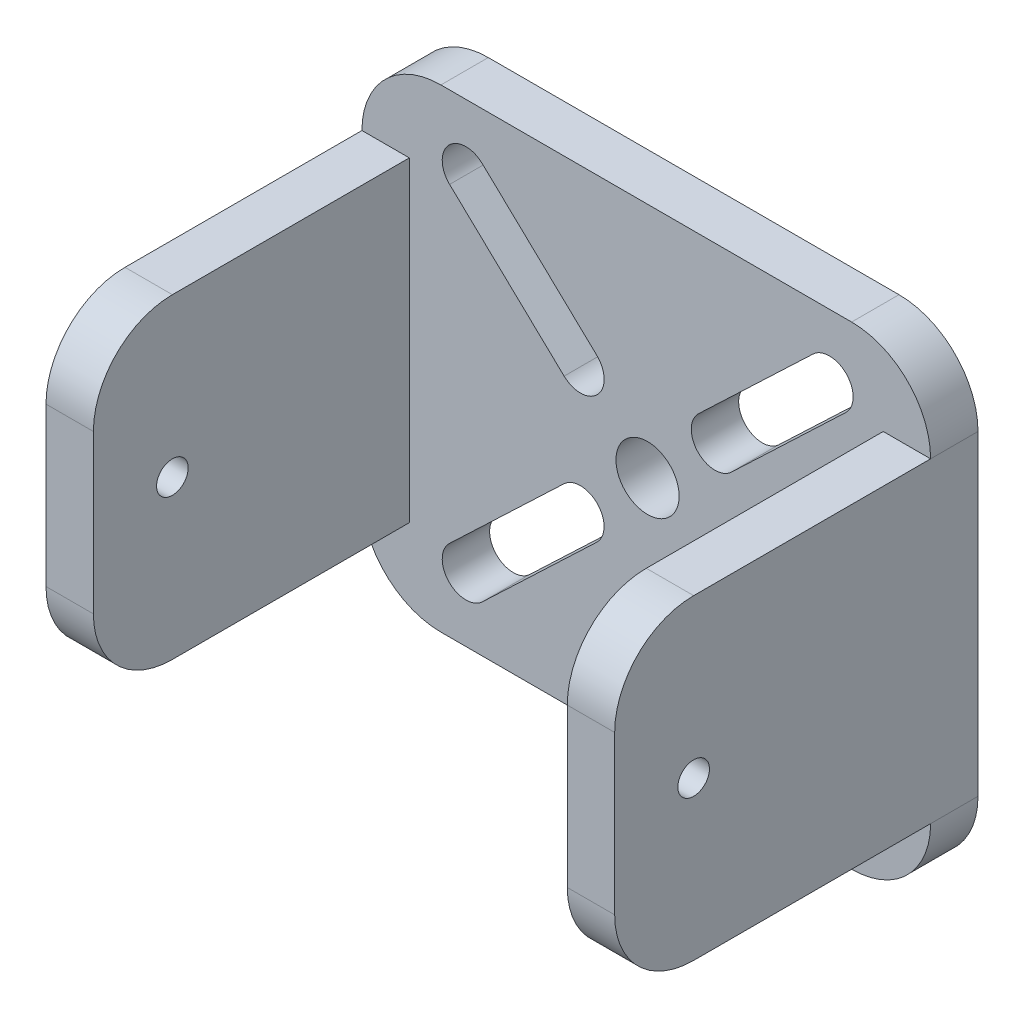
SolidWorks part; units mm, degrees
ref_plane "Front Plane" through (0, 0, 0) normal (0, 0, 1) x (1, 0, 0)
ref_plane "Top Plane" through (0, 0, 0) normal (0, 1, 0) x (1, 0, 0)
ref_plane "Right Plane" through (0, 0, 0) normal (1, 0, 0) x (0, 0, -1)
sketch "Sketch1" plane through (0, 0, 0) normal (0, 0, 1) x (1, 0, 0)
  line L0 (2.297, 29.9783) -> (33.8639, 0)
  line L1 (0, 0) -> (36, 0)
  line L2 (0, 0) -> (0, 30)
  line L3 (0, 30) -> (36, 30)
  line L4 (36, 0) -> (36, 30)
  line L5 (2.297, -0.0217) -> (33.8639, 30)
  line L6 (33.8639, 30) -> (18.0804, 14.9891)
  line L7 (33.8639, 30) -> (18.0804, 14.9891)
  line L8 (29.5952, 25.9403) -> (22.349, 19.0488) construction
  line L9 (30.629, 24.8534) -> (23.3828, 17.9619)
  line L10 (28.5615, 27.0272) -> (21.3153, 20.1357)
  line L11 (22.349, 10.9353) -> (29.6002, 4.0491) construction
  line L12 (23.382, 12.023) -> (30.6332, 5.1367)
  line L13 (21.3161, 9.8477) -> (28.5673, 2.9614)
  line L14 (13.8285, 10.9453) -> (6.5823, 4.0538) construction
  line L15 (14.8622, 9.8584) -> (7.616, 2.9669)
  line L16 (12.7947, 12.0322) -> (5.5486, 5.1407)
  line L17 (6.5823, 25.9087) -> (13.8335, 19.0224) construction
  line L18 (7.6152, 26.9963) -> (14.8664, 20.1101)
  line L19 (5.5493, 24.821) -> (12.8005, 17.9347)
  circle A0 centre (18.0804, 14.9891) radius 2
  arc A1 (30.629, 24.8534) -> (28.5615, 27.0272) centre (29.5952, 25.9403) ccw
  arc A2 (21.3153, 20.1357) -> (23.3828, 17.9619) centre (22.349, 19.0488) ccw
  arc A3 (23.382, 12.023) -> (21.3161, 9.8477) centre (22.349, 10.9353) ccw
  arc A4 (28.5673, 2.9614) -> (30.6332, 5.1367) centre (29.6002, 4.0491) ccw
  arc A5 (14.8622, 9.8584) -> (12.7947, 12.0322) centre (13.8285, 10.9453) ccw
  arc A6 (5.5486, 5.1407) -> (7.616, 2.9669) centre (6.5823, 4.0538) ccw
  arc A7 (7.6152, 26.9963) -> (5.5493, 24.821) centre (6.5823, 25.9087) ccw
  arc A8 (12.8005, 17.9347) -> (14.8664, 20.1101) centre (13.8335, 19.0224) ccw
  point P10 (18.0804, 14.9891)
  point P13 (18.0804, 14.9891)
  point P15 (25.9721, 22.4946)
  point P22 (25.9746, 7.4922)
  point P29 (10.2054, 7.4996)
  point P36 (10.2079, 22.4655)
  dimension "D1" = 30
  dimension "D2" = 36
extrude "Boss-Extrude2" add sketch "Sketch1" along normal blind 3
sketch "Sketch2" plane through (36, 0, 0) normal (1, 0, 0) x (0, 0, -1)
  line L0 (-3, 0) -> (-3, 30) construction
  line L1 (-18, 5) -> (-3, 5)
  line L2 (-23, 10) -> (-23, 20)
  line L3 (-18, 25) -> (-3, 25)
  line L4 (-3, 5) -> (-3, 25)
  line L5 (-23, 5) -> (-3, 25) construction
  line L6 (-23, 25) -> (-3, 5) construction
  circle A0 centre (-18, 15) radius 1
  arc A1 (-18, 5) -> (-23, 10) centre (-18, 10) cw
  arc A2 (-23, 20) -> (-18, 25) centre (-18, 20) cw
  point P0 (-13, 15)
  point P16 (0, 0)
  dimension "D4" = 2
  dimension "D6" = 5
  dimension "D1" = 20
  dimension "D2" = 5
  dimension "D3" = 20
  dimension "D5" = 15
extrude "Boss-Extrude3" add sketch "Sketch2" against normal blind 3
sketch "Sketch3" plane through (0, 0, 0) normal (-1, 0, 0) x (0, 0, 1)
  line L0 (3, 25) -> (18, 25)
  line L1 (23, 20) -> (23, 10)
  line L2 (18, 5) -> (3, 5)
  line L3 (3, 5) -> (3, 25)
  arc A0 (18, 25) -> (23, 20) centre (18, 20) cw
  arc A1 (23, 10) -> (18, 5) centre (18, 10) cw
  circle A2 centre (18, 15) radius 1
extrude "Boss-Extrude4" add sketch "Sketch3" against normal blind 3
fillet "Fillet1" radius 5 4 edges at (36, 30, 1.5) (0, 30, 1.5) (0, 0, 1.5) (36, 0, 1.5)
